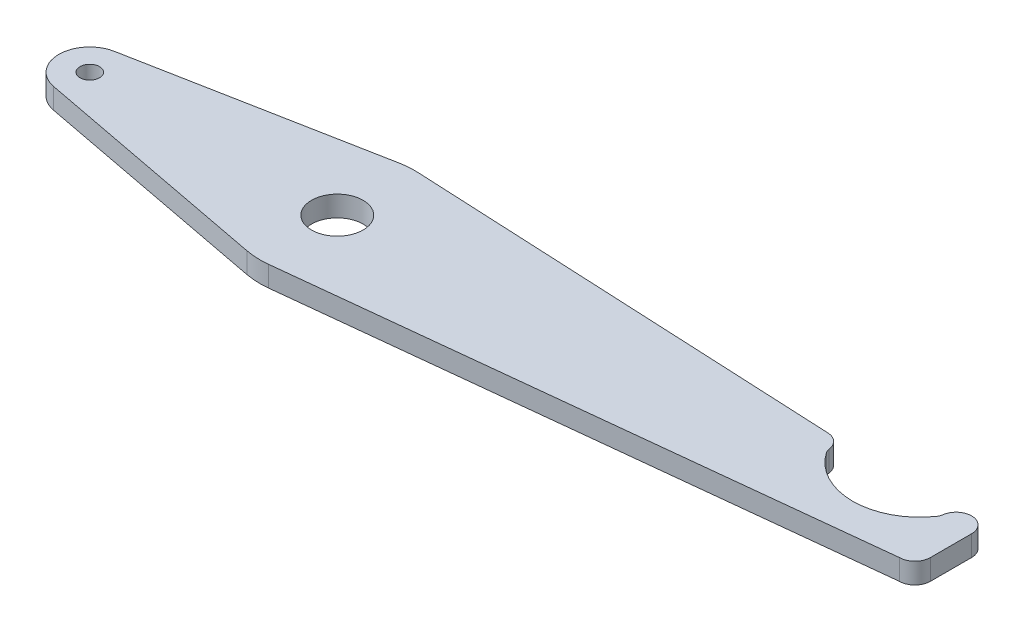
SolidWorks part; units mm, degrees
ref_plane "Front Plane" through (0, 0, 0) normal (0, 0, 1) x (1, 0, 0)
ref_plane "Top Plane" through (0, 0, 0) normal (0, 1, 0) x (1, 0, 0)
ref_plane "Right Plane" through (0, 0, 0) normal (1, 0, 0) x (0, 0, -1)
sketch "Sketch1" plane through (0, 0, 0) normal (0, 1, 0) x (1, 0, 0)
  line L0 (-38.993, 4.678) -> (-2.2324, 11.6951)
  line L1 (-38.993, -4.678) -> (-2.2324, -11.6951)
  line L2 (66.675, 0) -> (66.675, 6.35) construction
  line L3 (64.2938, 0) -> (64.2938, 6.35)
  line L4 (69.0563, 0) -> (69.0563, 6.35)
  line L7 (88.9, 0) -> (88.9, 6.35) construction
  line L10 (86.5187, 0) -> (86.5187, 6.35)
  line L11 (91.2812, 0) -> (91.2812, 6.35)
  line L12 (0, 0) -> (66.675, 0) construction
  line L13 (66.675, 0) -> (88.9, 0) construction
  line L14 (1.2775, -11.8375) -> (88.9, -2.3813)
  line L15 (0.5687, 11.8927) -> (66.675, 8.7313)
  line L16 (77.7875, 1.529) -> (78.3326, -3.5217) construction
  circle A0 centre (0, 0) radius 3.9688
  arc A1 (-2.2324, -11.6951) -> (1.2775, -11.8375) centre (0, 0) ccw
  arc A2 (-38.993, 4.678) -> (-38.993, -4.678) centre (-38.1, 0) ccw
  arc A6 (-38.993, -4.678) -> (-38.993, 4.678) centre (-38.1, 0) ccw construction
  circle A7 centre (-38.1, 0) radius 1.5
  arc A10 (64.2938, 0) -> (69.0563, 0) centre (66.675, 0) ccw
  arc A11 (69.0563, 6.35) -> (64.2938, 6.35) centre (66.675, 6.35) ccw
  arc A12 (86.5187, 0) -> (91.2812, 0) centre (88.9, 0) ccw
  arc A13 (91.2812, 6.35) -> (86.5187, 6.35) centre (88.9, 6.35) ccw
  arc A14 (69.0563, 6.35) -> (86.5187, 6.35) centre (77.7875, 11.846) ccw
  arc A15 (-2.2324, 11.6951) -> (-2.2324, -11.6951) centre (0, 0) ccw construction
  arc A16 (11.9063, 0) -> (0.5687, 11.8927) centre (0, 0) ccw construction
  arc A17 (0.5687, 11.8927) -> (-2.2324, 11.6951) centre (0, 0) ccw
  arc A18 (1.2775, -11.8375) -> (11.9063, 0) centre (0, 0) ccw construction
  point P12 (66.675, 3.175)
  point P17 (88.9, 3.175)
  point P35 (66.675, 8.7313)
  point P36 (0.4828, 11.336)
  dimension "D1" = 7.9375
  dimension "D3" = 88.9
  dimension "D4" = 9.525
  dimension "D7" = 6.35
  dimension "D9" = 7.9375
  dimension "D10" = 3
  dimension "D2" = 38.1
  dimension "D5" = 17.4625
  dimension "D6" = 4.7625
  dimension "D8" = 5.08
extrude "Boss-Extrude1" add sketch "Sketch1" along normal mid plane 3.175
fillet "Fillet1" radius 1.5875 2 edges at (86.5187, 0, -6.35) (69.0563, 0, -6.35)
